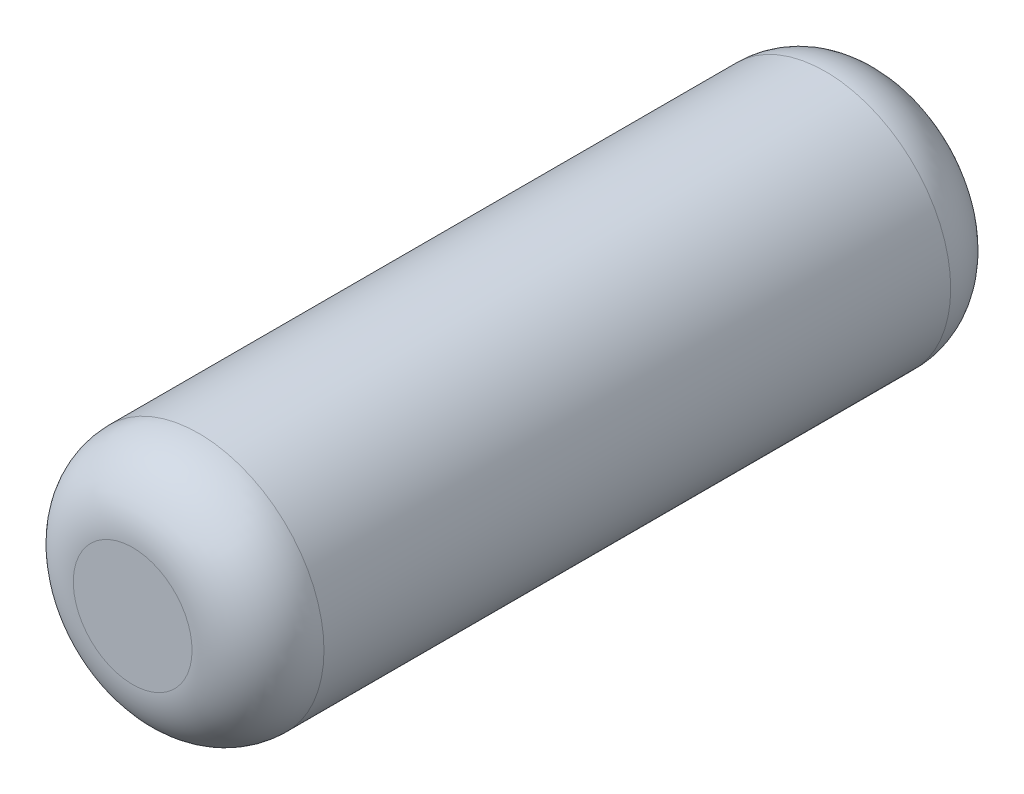
SolidWorks part; units mm, degrees
ref_plane "Front Plane" through (0, 0, 0) normal (0, 0, 1) x (1, 0, 0)
ref_plane "Top Plane" through (0, 0, 0) normal (0, 1, 0) x (1, 0, 0)
ref_plane "Right Plane" through (0, 0, 0) normal (1, 0, 0) x (0, 0, -1)
sketch "Sketch1" plane through (0, 0, 0) normal (0, 0, 1) x (1, 0, 0)
  circle A0 centre (0, 0) radius 48.26
  dimension "D1" = 96.52
extrude "Boss-Extrude1" add sketch "Sketch1" along normal blind 292.1
fillet "Fillet1" radius 25.4 2 edges at (48.26, 0, 0) (48.26, 0, 292.1)
